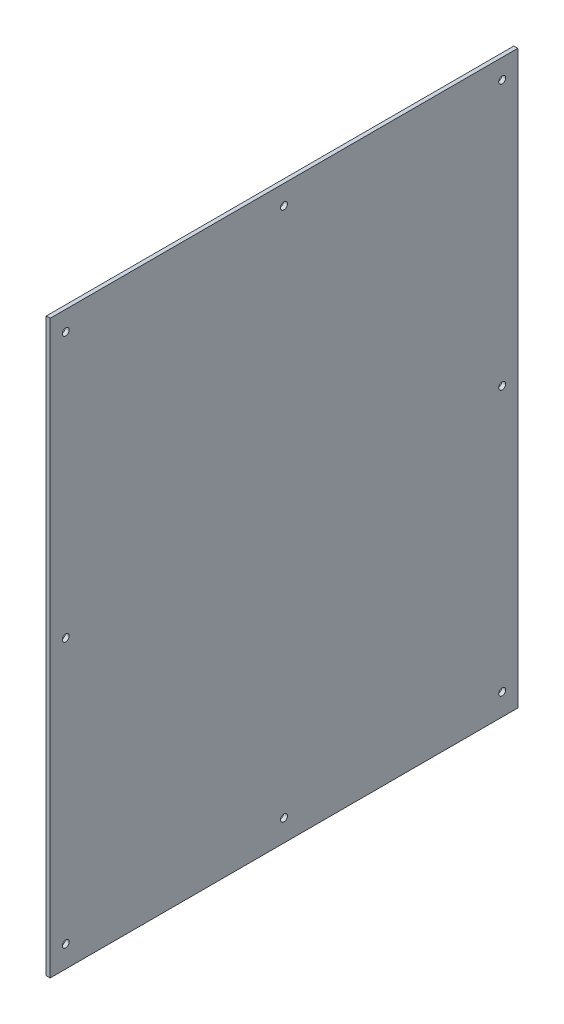
SolidWorks part; units mm, degrees
ref_plane "Front Plane" through (0, 0, 0) normal (1, 0, 0) x (0, 1, 0)
ref_plane "Top Plane" through (0, 0, 0) normal (0, 0, 1) x (0, 1, 0)
ref_plane "Right Plane" through (0, 0, 0) normal (0, 1, 0) x (-1, 0, 0)
sketch "Sketch1" plane through (0, 0, 0) normal (1, 0, 0) x (0, 1, 0)
  line L1 (-225, -187.5) -> (225, -187.5)
  line L2 (-225, -187.5) -> (-225, 187.5)
  line L3 (-225, 187.5) -> (225, 187.5)
  line L4 (225, -187.5) -> (225, 187.5)
  line L5 (-225, -187.5) -> (225, 187.5) construction
  line L6 (-225, 187.5) -> (225, -187.5) construction
  line L7 (-225, 187.5) -> (-230, 187.5)
  line L8 (-225, 187.5) -> (-225, -187.5)
  line L9 (-225, -187.5) -> (-230, -187.5)
  line L10 (-230, 187.5) -> (-230, -187.5)
  line L11 (-225, 187.5) -> (-230, -187.5) construction
  line L12 (-225, -187.5) -> (-230, 187.5) construction
  line L13 (225, -187.5) -> (228.175, -187.5)
  line L14 (225, -187.5) -> (225, 187.5)
  line L15 (225, 187.5) -> (228.175, 187.5)
  line L16 (228.175, -187.5) -> (228.175, 187.5)
  line L17 (225, -187.5) -> (228.175, 187.5) construction
  line L18 (225, 187.5) -> (228.175, -187.5) construction
  line L19 (212.5, -175) -> (-212.5, -175) construction
  line L20 (212.5, -175) -> (212.5, 175) construction
  line L21 (212.5, 175) -> (-212.5, 175) construction
  line L22 (-212.5, -175) -> (-212.5, 175) construction
  line L23 (212.5, -175) -> (-212.5, 175) construction
  line L24 (212.5, 175) -> (-212.5, -175) construction
  circle A0 centre (-212.5, 175) radius 2.8
  circle A1 centre (212.5, 175) radius 2.8
  circle A2 centre (212.5, -175) radius 2.8
  circle A3 centre (-212.5, -175) radius 2.8
  circle A4 centre (0, -175) radius 2.8
  circle A5 centre (0, 175) radius 2.8
  circle A6 centre (212.5, 0) radius 2.8
  circle A7 centre (-212.5, 0) radius 2.8
  point P0 (0, 0)
  point P8 (-227.5, 0)
  point P11 (226.5875, 0)
  point P12 (0, 0)
  dimension "D7" = 5.6
  dimension "D1" = 375
  dimension "D2" = 450
  dimension "D3" = 5
  dimension "D4" = 3.175
  dimension "D5" = 12.5
  dimension "D6" = 12.5
extrude "Boss-Extrude1" add sketch "Sketch1" along normal blind 3.175 contours L7 L10 L9 L2 | L1 L4 L3 L2 A7 A6 A5 A4 A3 A2 A1 A0 | L13 L16 L15 L4
